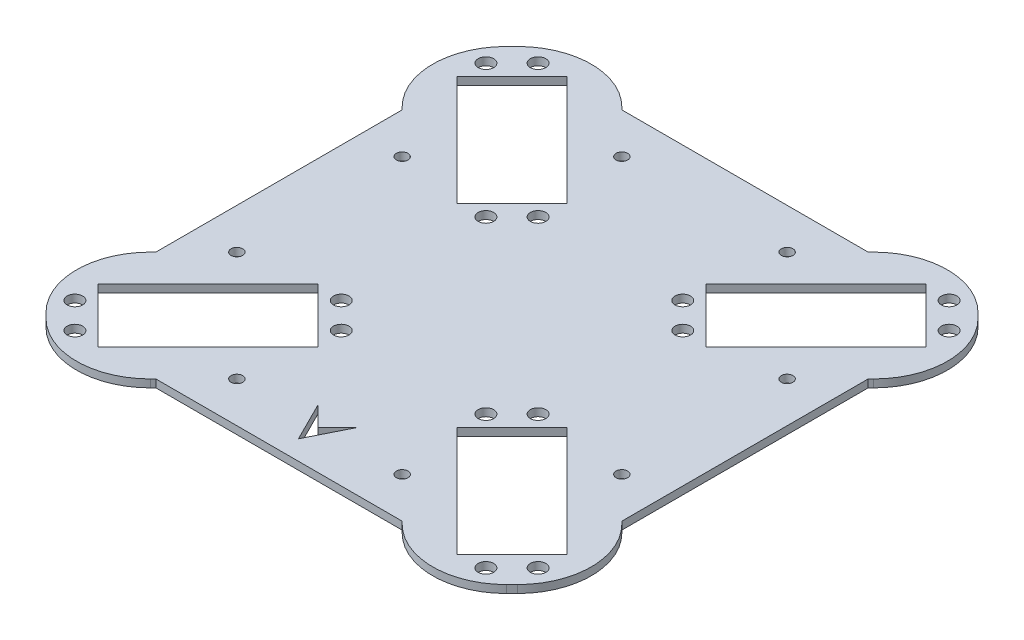
SolidWorks part; units mm, degrees
ref_plane "Front Plane" through (0, 0, 0) normal (0, 0, 1) x (1, 0, 0)
ref_plane "Top Plane" through (0, 0, 0) normal (0, 1, 0) x (1, 0, 0)
ref_plane "Right Plane" through (0, 0, 0) normal (1, 0, 0) x (0, 0, -1)
sketch "Sketch1" plane through (0, 0, 0) normal (0, 1, 0) x (1, 0, 0)
  line L1 (0, 0) -> (120, 0)
  line L2 (0, 0) -> (0, 120)
  line L3 (0, 120) -> (120, 120)
  line L4 (120, 0) -> (120, 120)
  dimension "D1" = 120
  dimension "D2" = 120
extrude "Boss-Extrude1" add sketch "Sketch1" along normal blind 2
sketch "Sketch2" plane through (0, 2, 0) normal (0, 1, 0) x (1, 0, 0)
  line L0 (60, 120) -> (60, 0) construction
  line L1 (120, 120) -> (0, 120) construction
  line L2 (0, 0) -> (120, 0) construction
  line L3 (120, 60) -> (0, 60) construction
  line L4 (120, 0) -> (120, 120) construction
  line L5 (0, 120) -> (0, 0) construction
  line L6 (60, 60) -> (120, 120) construction
  line L7 (105.8579, 105.8579) -> (120, 91.7157) construction
  line L8 (105.8579, 105.8579) -> (91.7157, 120) construction
  line L9 (91.7157, 120) -> (120, 91.7157)
  line L10 (91.7157, 120) -> (105.8579, 134.1421)
  line L11 (120, 91.7157) -> (134.1421, 105.8579)
  line L12 (105.8579, 134.1421) -> (134.1421, 105.8579)
  line L13 (0, 91.7157) -> (-14.1421, 105.8579)
  line L14 (14.1421, 134.1421) -> (-14.1421, 105.8579)
  line L15 (28.2843, 120) -> (14.1421, 134.1421)
  line L16 (28.2843, 120) -> (0, 91.7157)
  line L17 (28.2843, 0) -> (0, 28.2843)
  line L18 (28.2843, 0) -> (14.1421, -14.1421)
  line L19 (14.1421, -14.1421) -> (-14.1421, 14.1421)
  line L20 (0, 28.2843) -> (-14.1421, 14.1421)
  line L21 (120, 28.2843) -> (134.1421, 14.1421)
  line L22 (105.8579, -14.1421) -> (134.1421, 14.1421)
  line L23 (91.7157, 0) -> (105.8579, -14.1421)
  line L24 (91.7157, 0) -> (120, 28.2843)
  point P33 (120, 91.7157)
  point P34 (91.7157, 120)
  dimension "D1" = 40
  dimension "D2" = 20
extrude "Boss-Extrude3" add sketch "Sketch2" against normal blind 2
sketch "Sketch3" plane through (0, 2, 0) normal (0, 1, 0) x (1, 0, 0)
  line L0 (0, 0) -> (120, 120) construction
  line L1 (-14.1421, 14.1421) -> (14.1421, -14.1421) construction
  line L2 (134.1421, 105.8579) -> (105.8579, 134.1421) construction
  line L3 (0, 28.2843) -> (28.2843, 0) construction
  line L4 (6.7246, 6.7246) -> (20.8667, -7.4176) construction
  line L5 (14.1421, -14.1421) -> (28.2843, 0) construction
  line L6 (35.0089, 35.0089) -> (47.7718, 22.2459) construction
  line L7 (13.7957, -0.3465) -> (42.0799, 27.9378)
  line L8 (13.7957, -0.3465) -> (-0.3465, 13.7957)
  line L9 (42.0799, 27.9378) -> (27.9378, 42.0799)
  line L10 (-0.3465, 13.7957) -> (27.9378, 42.0799)
  line L11 (3.7194, 3.7194) -> (10.7828, -3.344) construction
  line L12 (27.9378, 13.7957) -> (13.7957, 27.9378) construction
  line L13 (0, 60) -> (120, 60) construction
  line L14 (0, 91.7157) -> (0, 28.2843) construction
  line L15 (120, 28.2843) -> (120, 91.7157) construction
  line L16 (60, 0) -> (60, 120) construction
  line L17 (28.2843, 0) -> (91.7157, 0) construction
  line L18 (91.7157, 120) -> (28.2843, 120) construction
  line L19 (77.9201, 27.9378) -> (92.0622, 42.0799)
  line L20 (120.3465, 13.7957) -> (92.0622, 42.0799)
  line L21 (106.2043, -0.3465) -> (120.3465, 13.7957)
  line L22 (106.2043, -0.3465) -> (77.9201, 27.9378)
  line L23 (106.2043, 120.3465) -> (77.9201, 92.0622)
  line L24 (106.2043, 120.3465) -> (120.3465, 106.2043)
  line L25 (120.3465, 106.2043) -> (92.0622, 77.9201)
  line L26 (77.9201, 92.0622) -> (92.0622, 77.9201)
  line L27 (42.0799, 92.0622) -> (27.9378, 77.9201)
  line L28 (-0.3465, 106.2043) -> (27.9378, 77.9201)
  line L29 (13.7957, 120.3465) -> (-0.3465, 106.2043)
  line L30 (13.7957, 120.3465) -> (42.0799, 92.0622)
  circle A0 centre (7.0781, 0.3606) radius 2
  circle A1 centre (0.3606, 7.0781) radius 2
  circle A2 centre (41.3728, 34.6553) radius 2
  circle A3 centre (34.6553, 41.3728) radius 2
  circle A4 centre (112.9219, 0.3606) radius 2
  circle A5 centre (119.6394, 7.0781) radius 2
  circle A6 centre (78.6272, 34.6553) radius 2
  circle A7 centre (85.3447, 41.3728) radius 2
  circle A8 centre (112.9219, 119.6394) radius 2
  circle A9 centre (119.6394, 112.9219) radius 2
  circle A10 centre (78.6272, 85.3447) radius 2
  circle A11 centre (85.3447, 78.6272) radius 2
  circle A12 centre (7.0781, 119.6394) radius 2
  circle A13 centre (0.3606, 112.9219) radius 2
  circle A14 centre (41.3728, 85.3447) radius 2
  circle A15 centre (34.6553, 78.6272) radius 2
  point P10 (14.1421, 14.1421)
  point P11 (35.0089, 35.0089)
  point P13 (6.7246, 6.7246)
  dimension "D5" = 4
  dimension "D6" = 9.5
  dimension "D7" = 4.25
  dimension "D1" = 29.51
  dimension "D2" = 10.49
  dimension "D3" = 20
  dimension "D4" = 4.25
extrude "Cut-Extrude1" cut sketch "Sketch3" against normal blind 2
fillet "Fillet1" radius 19 8 edges at (134.1421, 1, -14.1421) (105.8579, 1, 14.1421) (14.1421, 1, 14.1421) (-14.1421, 1, -14.1421) (-14.1421, 1, -105.8579) (14.1421, 1, -134.1421) (105.8579, 1, -134.1421) (134.1421, 1, -105.8579)
sketch "Sketch4" plane through (0, 2, 0) normal (0, 1, 0) x (1, 0, 0)
  line L0 (60, 120) -> (60, 0) construction
  line L1 (91.7157, 120) -> (28.2843, 120) construction
  line L2 (28.2843, 0) -> (91.7157, 0) construction
  line L3 (0, 60) -> (120, 60) construction
  line L4 (0, 91.7157) -> (0, 28.2843) construction
  line L5 (120, 28.2843) -> (120, 91.7157) construction
  line L6 (28.2843, 0) -> (60, 31.7157) construction
  line L7 (35.0089, 35.0089) -> (6.7246, 6.7246) construction
  line L8 (42.0799, 27.9378) -> (27.9378, 42.0799) construction
  line L9 (-0.3465, 13.7957) -> (13.7957, -0.3465) construction
  line L10 (42.0799, 27.9378) -> (28.2843, 0) construction
  line L11 (35.1821, 13.9689) -> (38.7176, 10.4334) construction
  line L12 (27.5772, -0.7071) -> (28.2843, 0) construction
  circle A0 centre (38.7176, 10.4334) radius 1.5
  circle A1 centre (10.4334, 38.7176) radius 1.5
  circle A2 centre (81.2824, 10.4334) radius 1.5
  circle A3 centre (109.5666, 38.7176) radius 1.5
  circle A4 centre (38.7176, 109.5666) radius 1.5
  circle A5 centre (10.4334, 81.2824) radius 1.5
  circle A6 centre (81.2824, 109.5666) radius 1.5
  circle A7 centre (109.5666, 81.2824) radius 1.5
  dimension "D1" = 3
extrude "Cut-Extrude2" cut sketch "Sketch4" against normal blind 2
sketch "Sketch5" plane through (0, 2, 0) normal (0, 1, 0) x (1, 0, 0)
  line L0 (60, 0) -> (60, 120) construction
  line L1 (28.2843, 0) -> (91.7157, 0) construction
  line L2 (91.7157, 120) -> (28.2843, 120) construction
  line L3 (60, 15) -> (65, 15) construction
  line L4 (65, 15) -> (60, 10)
  line L5 (65, 15) -> (60, 5)
  line L6 (55, 15) -> (60, 5)
  line L7 (55, 15) -> (60, 10)
  dimension "D1" = 5
  dimension "D2" = 5
  dimension "D3" = 10
  dimension "D4" = 5
extrude "Cut-Extrude3" cut sketch "Sketch5" against normal blind 2
